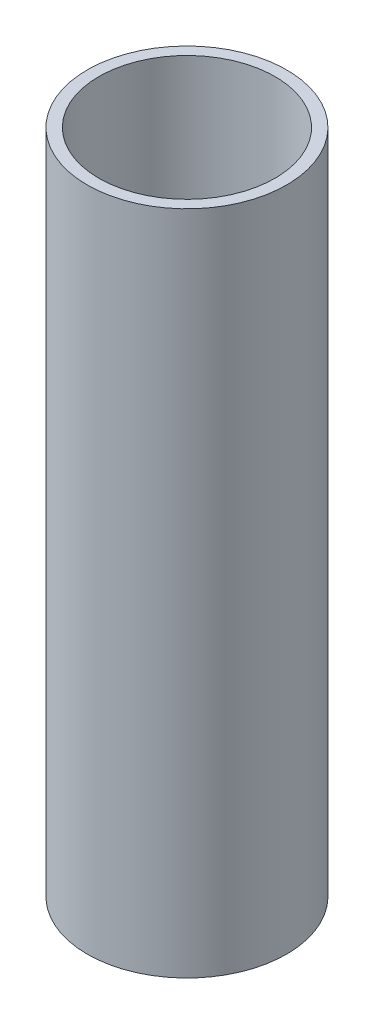
SolidWorks part; units mm, degrees
ref_plane "Front Plane" through (0, 0, 0) normal (0, 0, 1) x (1, 0, 0)
ref_plane "Top Plane" through (0, 0, 0) normal (0, 1, 0) x (1, 0, 0)
ref_plane "Right Plane" through (0, 0, 0) normal (1, 0, 0) x (0, 0, -1)
sketch "Sketch1" plane through (0, 0, 0) normal (0, 1, 0) x (1, 0, 0)
  circle A0 centre (0, 0) radius 3.0036
  dimension "D1" = 6.0071
extrude "Boss-Extrude1" add sketch "Sketch1" along normal mid plane 20.066
hole_wizard "#4 (0.209) Diameter Hole1" positions "Sketch4" profile "Sketch6" hole size "#4" standard "ANSI Inch" end condition through all
sketch "Sketch4" plane through (0, 10.033, 0) normal (0, 1, 0) x (1, 0, 0)
  point P0 (0, 0)
sketch "Sketch6" plane through (0, 10.033, 0) normal (1, 0, 0) x (0, 0, 1)
  line L0 (0, 0) -> (0, 20.066)
  line L1 (0, 20.066) -> (2.6543, 20.066)
  line L2 (2.6543, 20.066) -> (2.6543, 0)
  line L5 (2.6543, 0) -> (0, 0)
  line L11 (0, -6.35) -> (0, 107.95) construction
  dimension "Thru Hole Dia." = 5.3086
  dimension "Thru Hole Depth" = 20.066
